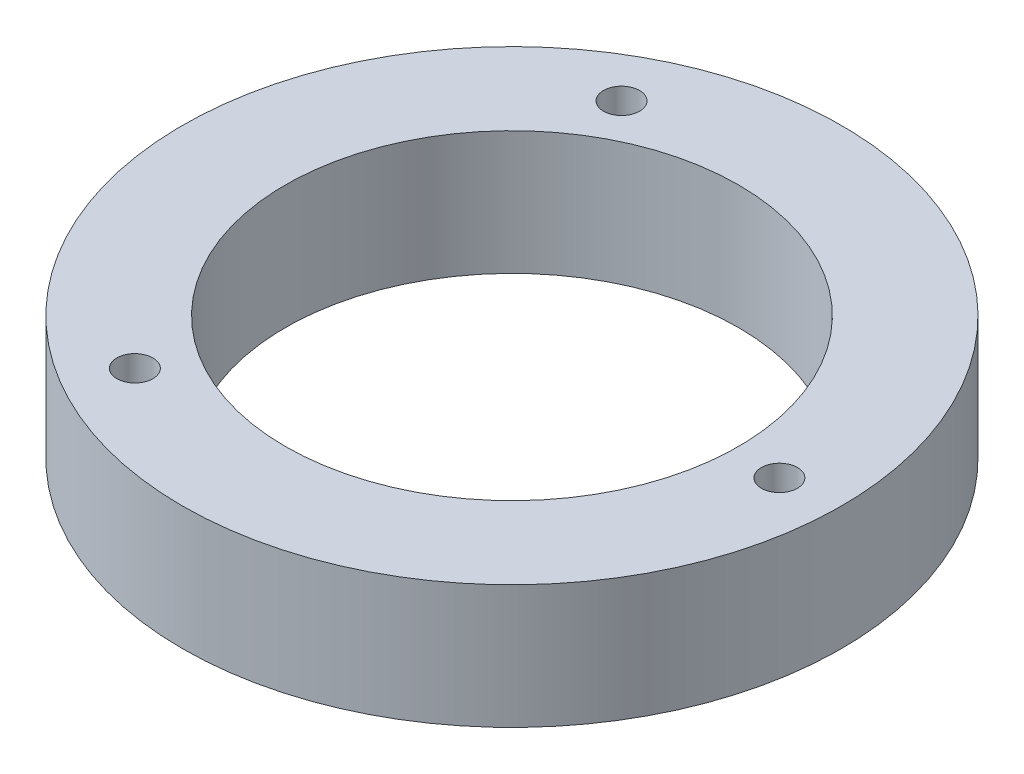
SolidWorks part; units mm, degrees
ref_plane "Front Plane" through (0, 0, 0) normal (0, 0, 1) x (1, 0, 0)
ref_plane "Top Plane" through (0, 0, 0) normal (0, 1, 0) x (1, 0, 0)
ref_plane "Right Plane" through (0, 0, 0) normal (1, 0, 0) x (0, 0, -1)
sketch "Sketch1" plane through (0, 0, 0) normal (0, 1, 0) x (1, 0, 0)
  circle A0 centre (0, 0) radius 22
  circle A1 centre (0, 0) radius 32
  circle A5 centre (0.0465, 0.3598) radius 22 construction
  circle A6 centre (26.6257, -0.6554) radius 1.75
  circle A7 centre (-13.8804, -22.7308) radius 1.75
  circle A8 centre (-12.7453, 23.3862) radius 1.75
  point P12 (0, 0)
  point P17 (0, 0)
  dimension "D1" = 3
extrude "Boss-Extrude1" add sketch "Sketch1" along normal blind 12
